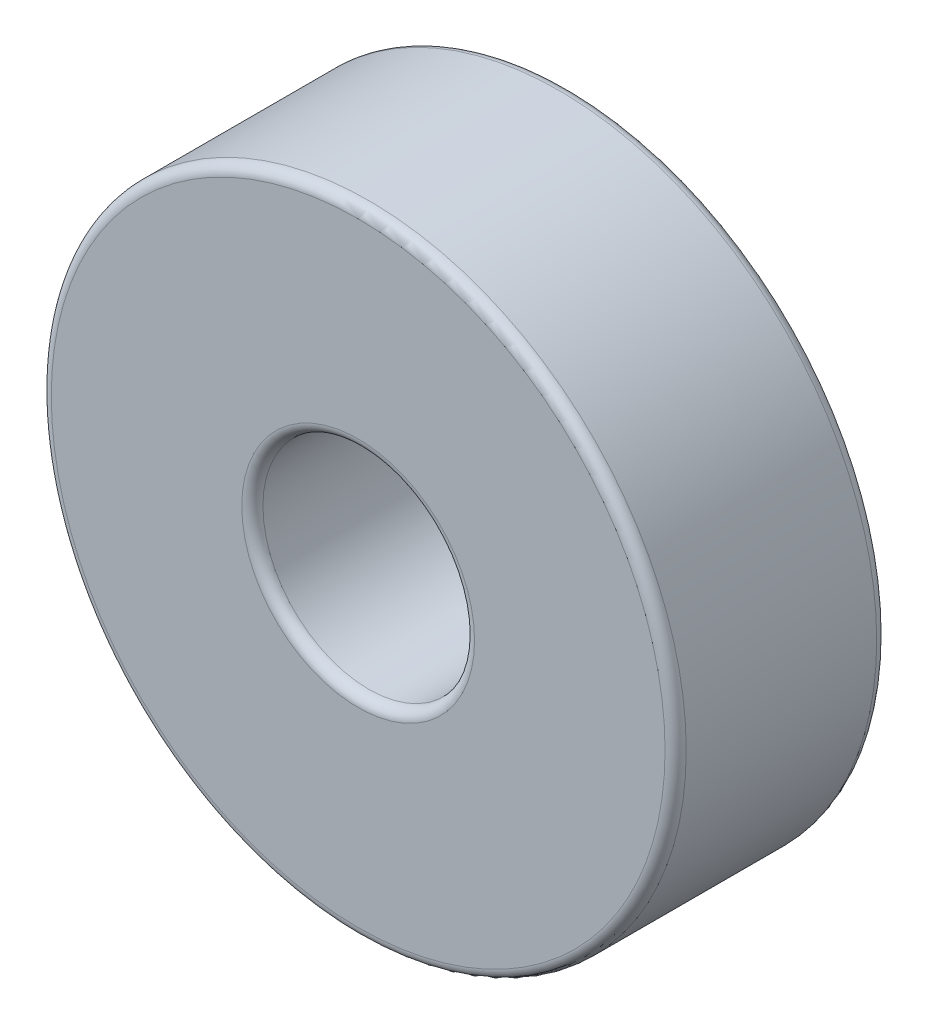
SolidWorks part; units mm, degrees
ref_plane "前视基准面" through (0, 0, 0) normal (0, 0, 1) x (1, 0, 0)
ref_plane "上视基准面" through (0, 0, 0) normal (0, 1, 0) x (1, 0, 0)
ref_plane "右视基准面" through (0, 0, 0) normal (1, 0, 0) x (0, 0, -1)
sketch "草图1" plane through (0, 0, 0) normal (0, 0, 1) x (1, 0, 0)
  circle A0 centre (0, 0) radius 4.5
  circle A1 centre (0, 0) radius 1.5
  dimension "D1" = 9
  dimension "D2" = 3
extrude "凸台-拉伸1" add sketch "草图1" along normal blind 3
fillet "圆角1" radius 0.15 4 edges at (1.5, 0, 0) (1.5, 0, 3) (4.5, 0, 0) (4.5, 0, 3)
